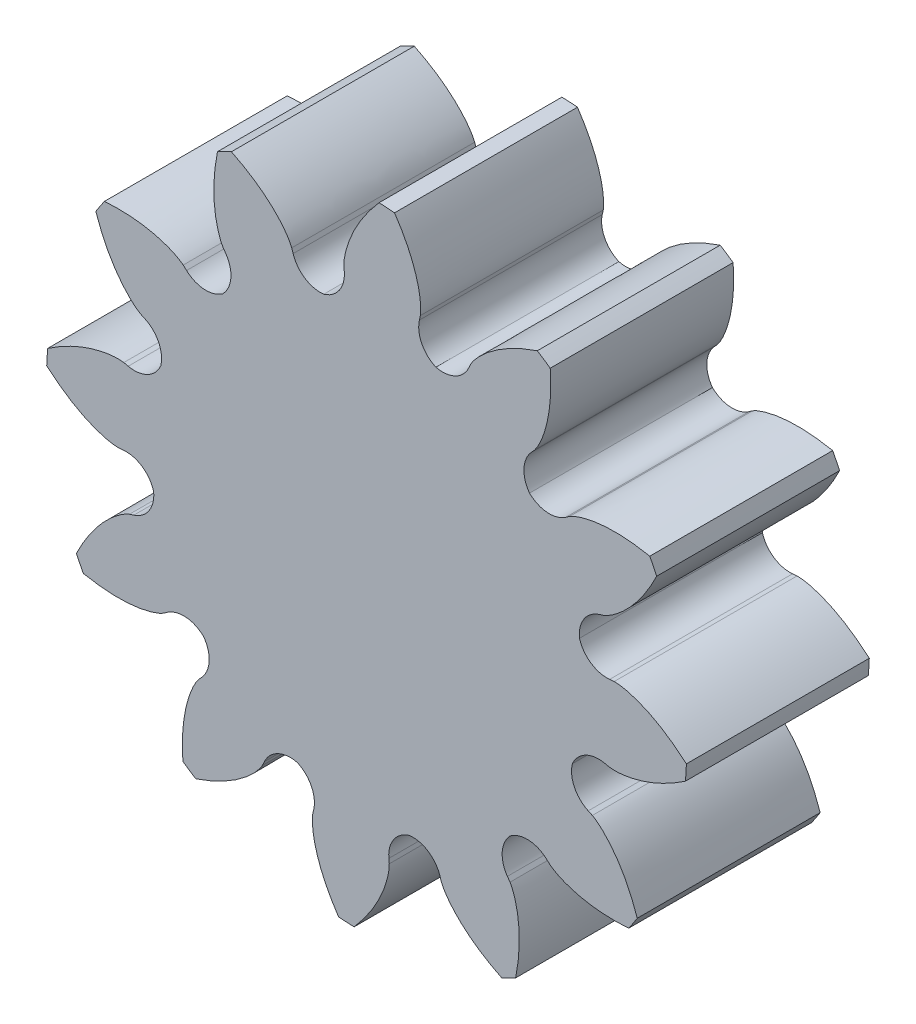
SolidWorks part; units mm, degrees
ref_plane "Front Plane" through (0, 0, 0) normal (0, 0, 1) x (1, 0, 0)
ref_plane "Top Plane" through (0, 0, 0) normal (0, 1, 0) x (1, 0, 0)
ref_plane "Right Plane" through (0, 0, 0) normal (1, 0, 0) x (0, 0, -1)
sketch "Sketch1" plane through (0, 0, 0) normal (0, 0, 1) x (1, 0, 0)
  circle A0 centre (0, 0) radius 7.5406
  dimension "D1" = 15.0812
extrude "Boss-Extrude1" add sketch "Sketch1" along normal blind 6.35
sketch "Sketch2" plane through (0, 0, 6.35) normal (0, 0, 1) x (1, 0, 0)
  line L0 (0, 0) -> (0.4294, 8.6219) construction
  line L1 (0, 0) -> (1.8679, 8.4281) construction
  line L2 (0, 0) -> (-1.0211, 8.572) construction
  line L3 (0, 0) -> (-2.4428, 8.2797) construction
  line L4 (0, 0) -> (-3.7955, 7.7534) construction
  line L5 (1.8679, 8.4281) -> (0.4294, 8.6219) construction
  line L6 (0.4294, 8.6219) -> (-1.0211, 8.572) construction
  line L7 (-1.0211, 8.572) -> (-2.4428, 8.2797) construction
  line L8 (-2.4428, 8.2797) -> (-3.7955, 7.7534) construction
  line L9 (0, 0) -> (-5.0408, 7.008) construction
  line L10 (-5.0408, 7.008) -> (-3.7955, 7.7534) construction
  line L11 (0.4294, 8.6219) -> (1.8791, 8.5497) construction
  line L12 (-1.0211, 8.572) -> (1.8613, 8.9154) construction
  line L13 (-2.4428, 8.2797) -> (1.7335, 9.5119) construction
  line L14 (-3.7955, 7.7534) -> (1.419, 10.306) construction
  line L15 (-5.0408, 7.008) -> (0.8505, 11.2456) construction
  line L16 (0, 0) -> (0.7032, 11.0902) construction
  line L17 (0, 0) -> (1.776, 9.358) construction
  line L20 (0, 0) -> (2.4087, 7.1456) construction
  line L23 (1.8679, 8.4281) -> (1.8337, 8.2741)
  line L25 (-0.7883, 8.5965) -> (-0.7739, 8.4394)
  circle A0 centre (0, 0) radius 8.6326 construction
  circle A1 centre (0, 0) radius 9.525 construction
  circle A2 centre (0, 0) radius 11.1125 construction
  arc A3 (0.4336, 11.104) -> (0.9724, 11.0699) centre (0, 0) cw
  circle A5 centre (0, 0) radius 7.5406 construction
  arc A6 (1.808, 7.3207) -> (-0.8689, 7.4904) centre (0, 0) ccw
  arc A7 (1.8337, 8.2741) -> (2.4087, 7.1456) centre (2.8059, 8.0586) ccw
  arc A8 (-0.7739, 8.4394) -> (-1.4868, 7.3926) centre (-1.7655, 8.3485) cw
  circle A9 centre (0, 0) radius 7.5406 construction
  spline S0 degree 3 poles (1.8679, 8.4281) (1.89, 8.5897) (1.8714, 8.9582) (1.6489, 9.9542) (1.2267, 10.7184) (0.8505, 11.2456) knots 0 0 0 0 0.160037 0.360032 1 1 1 1 construction
  spline S1 degree 3 poles (1.8679, 8.4281) (1.89, 8.5896) (1.8741, 8.9048) (1.803, 9.2647) (1.5938, 10.0196) (1.2951, 10.5912) (0.9724, 11.0699) knots 0 0 0 0 0.172051 0.330899 0.38719 1 1 1 1
  spline S2 degree 3 poles (1.808, 7.3207) (1.9942, 7.2742) (2.3008, 7.1925) (2.4087, 7.1456) knots 0 0 0 0 1 1 1 1
  spline S3 degree 3 poles (-0.7883, 8.5965) (-0.7899, 8.7596) (-0.7343, 9.0702) (-0.6183, 9.4182) (-0.3154, 10.1406) (0.0531, 10.67) (0.4336, 11.104) knots 0 0 0 0 0.172051 0.330899 0.38719 1 1 1 1
  spline S4 degree 3 poles (-0.8689, 7.4904) (-1.0594, 7.4679) (-1.3739, 7.4255) (-1.4868, 7.3926) knots 0 0 0 0 1 1 1 1
  dimension "D1" = 17.2652
  dimension "D2" = 19.05
  dimension "D3" = 22.225
  dimension "D4" = 1.4514
  dimension "D5" = 2.9029
  dimension "D6" = 4.3543
  dimension "D7" = 5.8057
  dimension "D8" = 7.2571
  dimension "D9" = 7.118
  dimension "D10" = 15
extrude "Boss-Extrude2" add sketch "Sketch2" against normal blind 6.35
pattern_circular "CirPattern1" count 12 every 30 about axis through (0, 0, 6.35) along (0, 0, -1) of "Boss-Extrude2"
equation "\"value\"=0.0571429"
equation "\"D4@Sketch2\"=\"value\""
equation "\"D5@Sketch2\"=\"value\"*2"
equation "\"D6@Sketch2\"=\"value\"*3"
equation "\"D7@Sketch2\"=\"value\"*4"
equation "\"D8@Sketch2\"=\"value\"*5"
